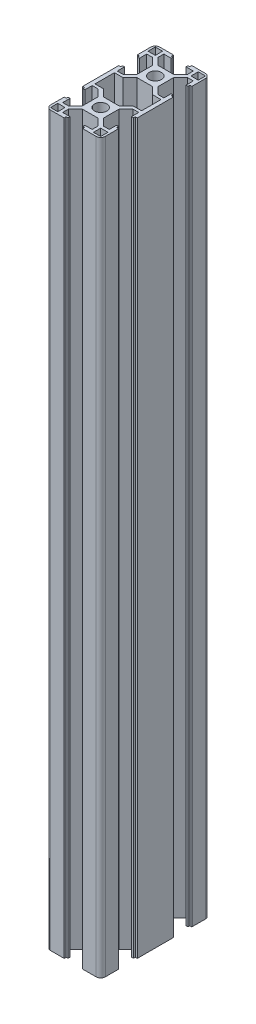
SolidWorks part; units mm, degrees
ref_plane "Front Plane" through (0, 0, 0) normal (0, 0, 1) x (1, 0, 0)
ref_plane "Top Plane" through (0, 0, 0) normal (0, 1, 0) x (1, 0, 0)
ref_plane "Right Plane" through (0, 0, 0) normal (1, 0, 0) x (0, 0, -1)
sketch "Sketch1" plane through (0, 0, 0) normal (0, 1, 0) x (1, 0, 0)
  line L0 (0, 0) -> (0, 15) construction
  line L6 (0, 15) -> (0, 37.9836) construction
  line L7 (0, 15) -> (33.3125, 15) construction
  line L19 (0, 15) -> (27.8511, 42.8511) construction
  line L20 (-4.2444, 20.8) -> (4.2444, 20.8)
  line L21 (5.8, 10.7556) -> (5.8, 19.2444)
  line L22 (8.1, 24.6556) -> (8.1, 27.8)
  line L23 (8.1, 27.8) -> (4.1, 27.8)
  line L24 (4.1, 27.8) -> (4.1, 28.9)
  line L25 (4.1, 28.9) -> (5.1, 28.9)
  line L26 (5.1, 28.9) -> (5.1, 30)
  line L27 (5.1, 30) -> (13.4444, 30)
  line L28 (13.4444, 30) -> (15, 30)
  line L29 (15, 28.4444) -> (15, 30)
  line L30 (9.8, 24.8) -> (13.8, 24.8)
  line L31 (9.8, 24.8) -> (9.8, 28.8)
  line L32 (9.8, 28.8) -> (13.8, 28.8)
  line L33 (13.8, 24.8) -> (13.8, 28.8)
  line L34 (9.8, 24.8) -> (13.8, 28.8) construction
  line L35 (9.8, 28.8) -> (13.8, 24.8) construction
  line L36 (15, 20.1) -> (15, 28.4444)
  line L37 (4.2444, 20.8) -> (8.1, 24.6556)
  line L38 (5.8, 19.2444) -> (9.6556, 23.1)
  line L39 (13.9, 20.1) -> (15, 20.1)
  line L40 (13.9, 19.1) -> (13.9, 20.1)
  line L41 (12.8, 19.1) -> (13.9, 19.1)
  line L42 (12.8, 23.1) -> (12.8, 19.1)
  line L43 (9.6556, 23.1) -> (12.8, 23.1)
  line L44 (8.1, 5.3444) -> (12.8, 5.3444)
  line L46 (9.6556, 6.9) -> (12.8, 6.9)
  line L47 (12.8, 6.9) -> (12.8, 10.9)
  line L48 (12.8, 10.9) -> (13.9, 10.9)
  line L49 (13.9, 10.9) -> (13.9, 9.9)
  line L50 (13.9, 9.9) -> (15, 9.9)
  line L51 (5.8, 10.7556) -> (9.6556, 6.9)
  line L52 (4.2444, 9.2) -> (8.1, 5.3444)
  line L53 (15, 9.9) -> (15, 1.5556)
  line L58 (15, 1.5556) -> (15, 0)
  line L59 (13.4444, 0) -> (15, 0)
  line L60 (12.8, 0) -> (13.4444, 0)
  line L66 (-4.2444, 9.2) -> (4.2444, 9.2)
  line L67 (12.8, 5.3444) -> (12.8, 0)
  line L68 (-12.8, 5.3444) -> (-12.8, 0)
  line L69 (-9.8, 28.8) -> (-13.8, 24.8) construction
  line L70 (-9.8, 24.8) -> (-13.8, 28.8) construction
  line L76 (-12.8, 0) -> (-13.4444, 0)
  line L77 (-13.4444, 0) -> (-15, 0)
  line L78 (-15, 1.5556) -> (-15, 0)
  line L83 (-15, 9.9) -> (-15, 1.5556)
  line L84 (-4.2444, 9.2) -> (-8.1, 5.3444)
  line L85 (-5.8, 10.7556) -> (-9.6556, 6.9)
  line L86 (-13.9, 9.9) -> (-15, 9.9)
  line L87 (-13.9, 10.9) -> (-13.9, 9.9)
  line L88 (-12.8, 10.9) -> (-13.9, 10.9)
  line L89 (-12.8, 6.9) -> (-12.8, 10.9)
  line L90 (-9.6556, 6.9) -> (-12.8, 6.9)
  line L91 (-9.6556, 23.1) -> (-12.8, 23.1)
  line L92 (-12.8, 23.1) -> (-12.8, 19.1)
  line L93 (-12.8, 19.1) -> (-13.9, 19.1)
  line L94 (-13.9, 19.1) -> (-13.9, 20.1)
  line L95 (-13.9, 20.1) -> (-15, 20.1)
  line L96 (-5.8, 19.2444) -> (-9.6556, 23.1)
  line L97 (-4.2444, 20.8) -> (-8.1, 24.6556)
  line L98 (-15, 20.1) -> (-15, 28.4444)
  line L99 (-13.8, 24.8) -> (-13.8, 28.8)
  line L100 (-9.8, 28.8) -> (-13.8, 28.8)
  line L101 (-9.8, 24.8) -> (-9.8, 28.8)
  line L102 (-9.8, 24.8) -> (-13.8, 24.8)
  line L103 (-15, 28.4444) -> (-15, 30)
  line L104 (-13.4444, 30) -> (-15, 30)
  line L105 (-5.1, 30) -> (-13.4444, 30)
  line L106 (-5.1, 28.9) -> (-5.1, 30)
  line L107 (-4.1, 28.9) -> (-5.1, 28.9)
  line L108 (-4.1, 27.8) -> (-4.1, 28.9)
  line L109 (-8.1, 27.8) -> (-4.1, 27.8)
  line L110 (-8.1, 24.6556) -> (-8.1, 27.8)
  line L111 (-5.8, 10.7556) -> (-5.8, 19.2444)
  line L112 (-8.1, 5.3444) -> (-12.8, 5.3444)
  circle A1 centre (0, 15) radius 3.4
  point P2 (-5.8, 15)
  point P13 (11.8, 26.8)
  point P51 (5.8, 15)
  point P61 (0, 9.2)
  point P95 (0, 20.8)
  point P96 (-11.8, 26.8)
  dimension "D2" = 6.8
  dimension "D1" = 15
  dimension "D3" = 9.2
  dimension "D7" = 4
  dimension "D8" = 4.1
  dimension "D9" = 5.1
  dimension "D10" = 1.1
  dimension "D11" = 1.1
  dimension "D12" = 15
  dimension "D13" = 4
  dimension "D14" = 1.2
  dimension "D5" = 4
extrude "Boss-Extrude1" add sketch "Sketch1" along normal blind 400
fillet "Fillet1" radius 2.5 2 edges at (-15, 200, -30) (15, 200, -30)
mirror "Mirror1" about plane through (0, 0, 0) normal (0, 0, 1) of "Fillet1", "Boss-Extrude1"
